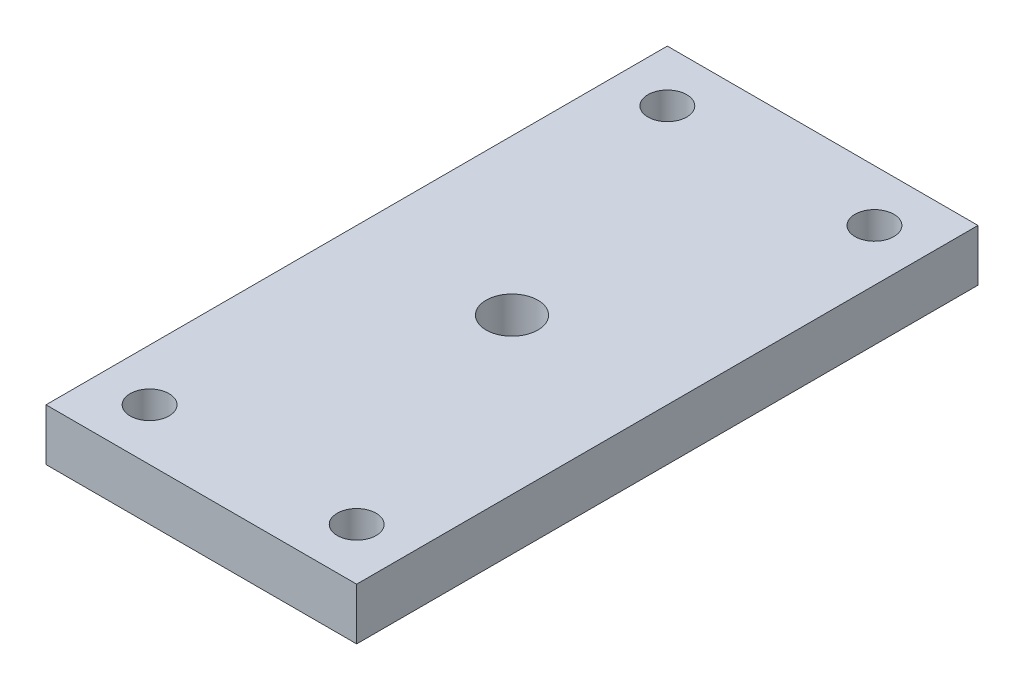
SolidWorks part; units mm, degrees
ref_plane "Front Plane" through (0, 0, 0) normal (0, 0, 1) x (1, 0, 0)
ref_plane "Top Plane" through (0, 0, 0) normal (0, 1, 0) x (1, 0, 0)
ref_plane "Right Plane" through (0, 0, 0) normal (1, 0, 0) x (0, 0, -1)
sketch "Sketch1" plane through (0, 0, 0) normal (0, 1, 0) x (1, 0, 0)
  line L1 (38.1, -76.2) -> (-38.1, -76.2)
  line L2 (38.1, -76.2) -> (38.1, 76.2)
  line L3 (38.1, 76.2) -> (-38.1, 76.2)
  line L4 (-38.1, -76.2) -> (-38.1, 76.2)
  line L5 (38.1, -76.2) -> (-38.1, 76.2) construction
  line L6 (38.1, 76.2) -> (-38.1, -76.2) construction
  circle A0 centre (0, 0) radius 6.35
  point P0 (0, 0)
  dimension "D3" = 12.7
  dimension "D1" = 152.4
  dimension "D2" = 76.2
extrude "Boss-Extrude1" add sketch "Sketch1" along normal blind 12.7
sketch "Sketch2" plane through (0, 12.7, 0) normal (0, 1, 0) x (1, 0, 0)
  line L0 (-38.1, 76.2) -> (-38.1, -76.2) construction
  line L1 (-25.4, 63.5) -> (25.4, 63.5) construction
  line L2 (-25.4, 63.5) -> (-25.4, -63.5) construction
  line L3 (-25.4, -63.5) -> (25.4, -63.5) construction
  line L4 (25.4, 63.5) -> (25.4, -63.5) construction
  line L5 (38.1, 76.2) -> (-38.1, 76.2) construction
  circle A0 centre (-25.4, 63.5) radius 4.7625
  circle A1 centre (-25.4, -63.5) radius 4.7625
  circle A2 centre (25.4, -63.5) radius 4.7625
  circle A3 centre (25.4, 63.5) radius 4.7625
  point P12 (-25.4, 0)
  point P14 (0, 63.5)
  dimension "D1" = 9.525
  dimension "D3" = 12.7
  dimension "D2" = 12.7
extrude "Cut-Extrude1" cut sketch "Sketch2" against normal through all
